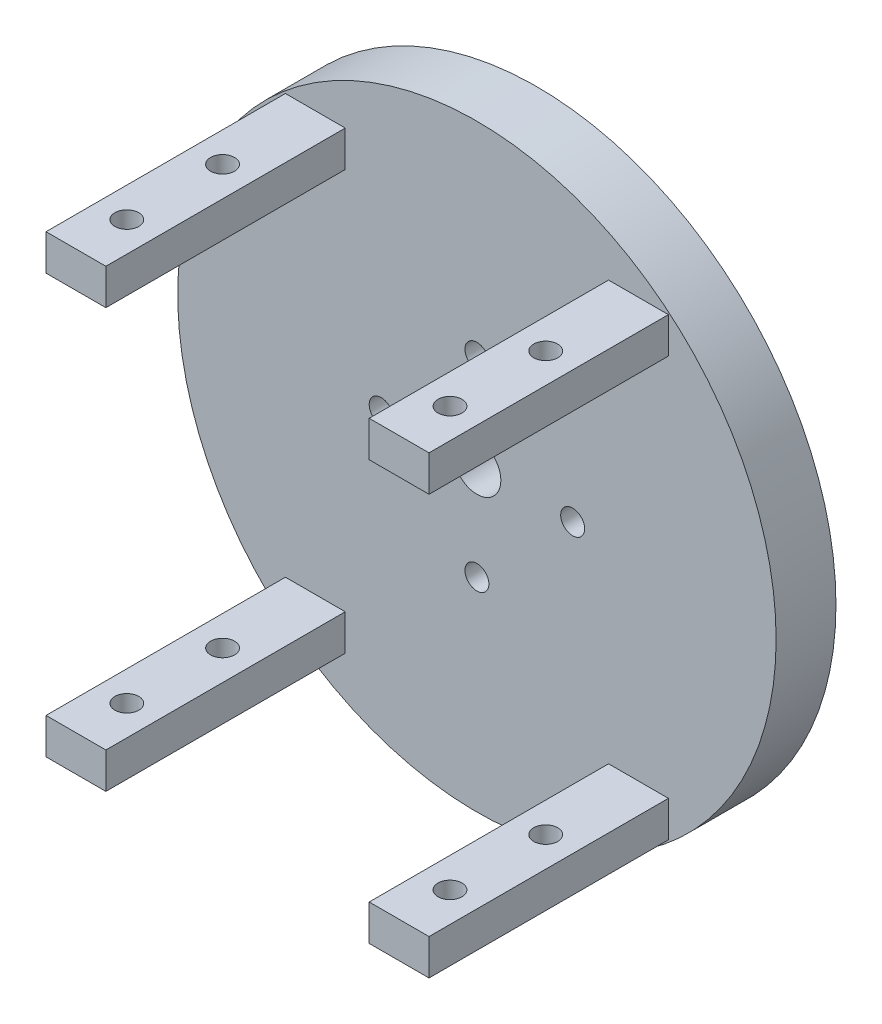
SolidWorks part; units mm, degrees
ref_plane "Front Plane" through (0, 0, 0) normal (0, 0, 1) x (1, 0, 0)
ref_plane "Top Plane" through (0, 0, 0) normal (0, 1, 0) x (1, 0, 0)
ref_plane "Right Plane" through (0, 0, 0) normal (1, 0, 0) x (0, 0, -1)
sketch "Sketch1" plane through (0, 0, 0) normal (0, 0, 1) x (1, 0, 0)
  line L0 (0, 0) -> (0, 8) construction
  circle A0 centre (0, 0) radius 25
  circle A1 centre (0, 8) radius 1
  circle A2 centre (8, 0) radius 1
  circle A3 centre (0, -8) radius 1
  circle A4 centre (-8, 0) radius 1
  circle A5 centre (0, 0) radius 2
  dimension "D1" = 50
  dimension "D2" = 2
  dimension "D3" = 4
  dimension "D5" = 8
  dimension "D4" = 4
extrude "Boss-Extrude1" add sketch "Sketch1" along normal blind 5
sketch "Sketch2" plane through (0, 0, 5) normal (0, 0, 1) x (1, 0, 0)
  line L0 (-11, 19) -> (-16, 19)
  line L1 (-11, 19) -> (11, 19) construction
  line L2 (-11, 19) -> (-11, 16)
  line L3 (-11, -19) -> (11, -19) construction
  line L4 (11, 19) -> (11, 16)
  line L5 (-11, 19) -> (11, -19) construction
  line L6 (-11, -19) -> (11, 19) construction
  line L7 (-16, 19) -> (-16, 16)
  line L8 (-16, -19) -> (-11, -19)
  line L9 (11, -19) -> (16, -19)
  line L10 (16, -19) -> (16, -16)
  line L11 (16, 19) -> (11, 19)
  line L12 (-16, 16) -> (-11, 16)
  line L13 (-16, -16) -> (-11, -16)
  line L14 (11, -16) -> (16, -16)
  line L15 (11, 16) -> (16, 16)
  line L16 (-16, -16) -> (-16, -19)
  line L17 (-11, -16) -> (-11, -19)
  line L18 (11, -16) -> (11, -19)
  line L19 (16, 16) -> (16, 19)
  point P0 (0, 0)
  dimension "D1" = 22
  dimension "D2" = 38
  dimension "D3" = 5
  dimension "D4" = 5
  dimension "D5" = 3
  dimension "D6" = 3
extrude "Boss-Extrude2" add sketch "Sketch2" along normal blind 20
sketch "Sketch3" plane through (0, -19, 0) normal (0, -1, 0) x (1, 0, 0)
  line L0 (-11, 5) -> (11, 5) construction
  circle A0 centre (-13.5, 20.75) radius 1
  circle A1 centre (-13.5, 12.75) radius 1
  circle A2 centre (13.5, 20.75) radius 1
  circle A3 centre (13.5, 12.75) radius 1
  point P8 (0, 0)
  point P9 (-13.4357, 15.3642)
  point P11 (0, 0)
  point P14 (0, 0)
  point P15 (13.5, 16.6186)
  dimension "D1" = 2
  dimension "D2" = 27
  dimension "D3" = 13.5
  dimension "D4" = 7.75
  dimension "D5" = 8
extrude "Cut-Extrude1" cut sketch "Sketch3" against normal through all
